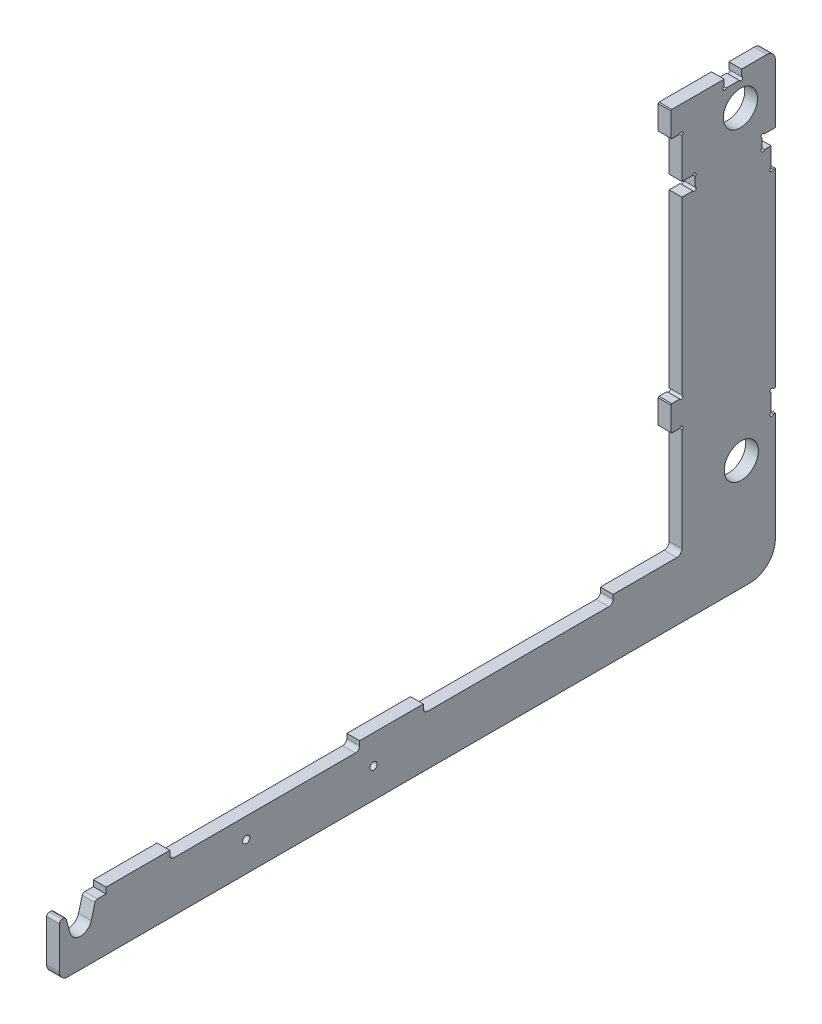
SolidWorks part; units mm, degrees
material "S355J2H"
ref_plane "Front Plane" through (0, 0, 0) normal (0, 0, 1) x (1, 0, 0)
ref_plane "Top Plane" through (0, 0, 0) normal (0, 1, 0) x (1, 0, 0)
ref_plane "Right Plane" through (0, 0, 0) normal (1, 0, 0) x (0, 0, -1)
sketch "Sketch1" plane through (0, 0, 0) normal (1, 0, 0) x (0, 0, -1)
  line L0 (-678, 0) -> (0, 0)
  line L1 (0, 0) -> (0, 460)
  line L2 (-678, 0) -> (-678, -69)
  line L4 (-678, -69) -> (110, -69)
  line L5 (110, -69) -> (110, 460)
  line L6 (110, 460) -> (0, 460)
  dimension "D1" = 678
  dimension "D2" = 460
  dimension "D3" = 110
  dimension "D4" = 69
extrude "Boss-Extrude1" add sketch "Sketch1" along normal blind 15
fillet "Fillet1" radius 30 1 edges at (7.5, -69, -110)
sketch "Sketch2" plane through (15, 0, 0) normal (1, 0, 0) x (0, 0, -1)
  line L0 (110, -39) -> (110, 460) construction
  line L2 (-678, -69) -> (80, -69) construction
  circle A0 centre (68.9, 421) radius 20.1
  circle A1 centre (69.9, 61) radius 20.1
  dimension "D1" = 40.2
  dimension "D2" = 41.1
  dimension "D5" = 40.1
  dimension "D3" = 130
  dimension "D4" = 490
extrude "Cut-Extrude1" cut sketch "Sketch2" against normal through all
fillet "Fillet2" radius 6 1 edges at (7.5, 0, 0)
sketch "Sketch4" plane through (0, 0, 0) normal (0, 0, 1) x (1, 0, 0)
  line L0 (15, 460) -> (15, 6) construction
  line L1 (0, 460) -> (15, 460)
  line L2 (0, 460) -> (0, 430)
  line L3 (0, 430) -> (15, 430)
  line L4 (15, 460) -> (15, 430)
  line L5 (0, 460) -> (0, 6) construction
  line L6 (0, 160) -> (15, 160)
  line L7 (0, 160) -> (0, 130)
  line L8 (0, 130) -> (15, 130)
  line L9 (15, 160) -> (15, 130)
  dimension "D1" = 30
  dimension "D2" = 300
extrude "Boss-Extrude2" add sketch "Sketch4" along normal blind 13
fillet "Fillet3" radius 10 1 edges at (7.5, 460, -110)
sketch "Sketch5" plane through (0, 0, 0) normal (-1, 0, 0) x (0, 0, 1)
  line L0 (-100, 460) -> (13, 460) construction
  line L1 (-70.25, 460) -> (-49.75, 460)
  line L2 (-70.25, 460) -> (-70.25, 449.75)
  line L3 (-70.25, 449.75) -> (-49.75, 449.75)
  line L4 (-49.75, 460) -> (-49.75, 449.75)
  line L5 (-110, -39) -> (-110, 450) construction
  dimension "D1" = 39.75
  dimension "D2" = 10.25
  dimension "D3" = 20.5
extrude "Cut-Extrude3" cut sketch "Sketch5" against normal through all
sketch "Sketch6" plane through (15, 0, 0) normal (1, 0, 0) x (0, 0, -1)
  line L0 (110, -39) -> (110, 450) construction
  line L1 (110, 380.5) -> (94.5, 380.5)
  line L2 (110, 380.5) -> (110, 364.5)
  line L3 (110, 364.5) -> (94.5, 364.5)
  line L4 (94.5, 380.5) -> (94.5, 364.5)
  line L5 (100, 460) -> (70.25, 460) construction
  line L6 (0, 430) -> (0, 160) construction
  line L7 (0, 380.5) -> (15.5, 380.5)
  line L8 (0, 380.5) -> (0, 364.5)
  line L9 (0, 364.5) -> (15.5, 364.5)
  line L10 (15.5, 380.5) -> (15.5, 364.5)
  line L11 (15.5, 380.5) -> (94.5, 380.5) construction
  dimension "D1" = 16
  dimension "D2" = 79.5
  dimension "D3" = 15.5
extrude "Cut-Extrude4" cut sketch "Sketch6" against normal through all
sketch "Sketch7" plane through (0, 0, 0) normal (-1, 0, 0) x (0, 0, 1)
  line L0 (-110, -39) -> (-110, 364.5) construction
  line L1 (-110, 364.5) -> (-105, 364.5)
  line L2 (-110, 364.5) -> (-110, 339)
  line L3 (-110, 339) -> (-105, 339)
  line L4 (-105, 364.5) -> (-105, 339)
  line L6 (-105, 89.5) -> (-105, 115.5)
  line L7 (-110, 115.5) -> (-105, 115.5)
  line L8 (-110, 89.5) -> (-110, 115.5)
  line L9 (-110, 89.5) -> (-105, 89.5)
  dimension "D1" = 25.5
  dimension "D2" = 5
  dimension "D3" = 275
  dimension "D4" = 26
  dimension "D5" = 5
extrude "Cut-Extrude5" cut sketch "Sketch7" against normal through all
chamfer "Chamfer1" distance 1 angle 45 4 edges at (7.5, 460, 13) (7.5, 130, 13) (7.5, 160, 13) (7.5, 430, 13)
sketch "Sketch8" plane through (15, 0, 0) normal (1, 0, 0) x (0, 0, -1)
  line L0 (-6, 0) -> (-678, 0) construction
  line L1 (-603, 0) -> (-379.5, 0)
  line L2 (-603, 0) -> (-603, -10)
  line L3 (-603, -10) -> (-379.5, -10)
  line L4 (-379.5, 0) -> (-379.5, -10)
  line L5 (-678, 0) -> (-678, -69) construction
  line L6 (-342, 0) -> (-342, -239.7246) construction
  line L7 (-304.5, 0) -> (-304.5, -10)
  line L8 (-81, -10) -> (-304.5, -10)
  line L9 (-81, 0) -> (-81, -10)
  line L10 (-81, 0) -> (-304.5, 0)
  dimension "D1" = 75
  dimension "D2" = 10
  dimension "D3" = 37.5
extrude "Cut-Extrude6" cut sketch "Sketch8" against normal up to surface (15 mm away) up to face at (0, 421, -89)
fillet "Fillet4" radius 5 4 edges at (7.5, -10, 603) (7.5, -10, 379.5) (7.5, -10, 304.5) (7.5, -10, 81)
sketch "Sketch9" plane through (15, 0, 0) normal (1, 0, 0) x (0, 0, -1)
  line L0 (-0.7071, 129.2929) -> (0, 130) construction
  line L1 (-12, 130) -> (0, 130) construction
  line L2 (-13, 145) -> (35.3065, 145) construction
  line L3 (-13, 131) -> (-13, 159) construction
  line L4 (-0.7071, 160.7071) -> (0, 160) construction
  line L5 (-0.7071, 429.2929) -> (0, 430) construction
  line L6 (-12, 430) -> (0, 430) construction
  circle A0 centre (-0.7071, 129.2929) radius 2
  circle A1 centre (-0.7071, 160.7071) radius 2
  circle A2 centre (-0.7071, 429.2929) radius 2
  dimension "D2" = 4
  dimension "D5" = 4
  dimension "D1" = 1
  dimension "D3" = 45
  dimension "D4" = 1
  dimension "D6" = 45
extrude "Cut-Extrude7" cut sketch "Sketch9" against normal through all
sketch "Sketch10" plane through (15, 0, 0) normal (1, 0, 0) x (0, 0, -1)
  line L0 (50.4571, 450.4571) -> (49.75, 449.75) construction
  line L1 (49.75, 449.75) -> (49.75, 460) construction
  line L2 (60, 449.75) -> (60, 463.7906) construction
  line L3 (70.25, 449.75) -> (49.75, 449.75) construction
  line L4 (69.5429, 450.4571) -> (70.25, 449.75) construction
  circle A0 centre (50.4571, 450.4571) radius 2
  circle A1 centre (69.5429, 450.4571) radius 2
  dimension "D2" = 4
  dimension "D1" = 1
  dimension "D3" = 45
extrude "Cut-Extrude8" cut sketch "Sketch10" against normal through all
sketch "Sketch11" plane through (15, 0, 0) normal (1, 0, 0) x (0, 0, -1)
  line L0 (14.7929, 365.2071) -> (15.5, 364.5) construction
  line L1 (0, 364.5) -> (15.5, 364.5) construction
  line L2 (15.5, 372.5) -> (-13.4221, 372.5) construction
  line L3 (15.5, 364.5) -> (15.5, 380.5) construction
  line L4 (14.7929, 379.7929) -> (15.5, 380.5) construction
  line L5 (55, 392.5692) -> (55, 339.5302) construction
  line L6 (95.2071, 379.7929) -> (94.5, 380.5) construction
  line L7 (94.5, 372.5) -> (123.4221, 372.5) construction
  line L8 (95.2071, 365.2071) -> (94.5, 364.5) construction
  circle A0 centre (14.7929, 365.2071) radius 2
  circle A1 centre (14.7929, 379.7929) radius 2
  circle A2 centre (95.2071, 379.7929) radius 2
  circle A3 centre (95.2071, 365.2071) radius 2
  dimension "D2" = 4
  dimension "D1" = 1
  dimension "D3" = 45
extrude "Cut-Extrude9" cut sketch "Sketch11" against normal through all
sketch "Sketch12" plane through (15, 0, 0) normal (1, 0, 0) x (0, 0, -1)
  line L0 (105.7071, 90.2071) -> (105, 89.5) construction
  line L1 (110, 89.5) -> (105, 89.5) construction
  line L2 (105, 102.5) -> (129.1199, 102.5) construction
  line L3 (105, 89.5) -> (105, 115.5) construction
  line L4 (105.7071, 114.7929) -> (105, 115.5) construction
  line L5 (105.7071, 339.7071) -> (105, 339) construction
  line L6 (105, 339) -> (105, 364.5) construction
  line L7 (110, 339) -> (105, 339) construction
  circle A0 centre (105.7071, 90.2071) radius 2
  circle A1 centre (105.7071, 114.7929) radius 2
  circle A2 centre (105.7071, 339.7071) radius 2
  dimension "D2" = 4
  dimension "D5" = 4
  dimension "D1" = 1
  dimension "D3" = 45
  dimension "D4" = 1
  dimension "D6" = 45
extrude "Cut-Extrude10" cut sketch "Sketch12" against normal through all
sketch "Sketch13" plane through (15, 0, 0) normal (1, 0, 0) x (0, 0, -1)
  line L0 (-678, -69) -> (-733, -69)
  line L1 (-733, -69) -> (-733, -7)
  line L2 (-733, -7) -> (-725.5, -7)
  line L3 (-725.5, -7) -> (-720.5532, -25.3788)
  line L4 (-695.4468, -25.3788) -> (-690.5, -7)
  line L5 (-690.5, -7) -> (-678, -7)
  line L6 (-678, -7) -> (-678, -69)
  line L7 (-678, 0) -> (-678, -69) construction
  line L8 (-603, 0) -> (-678, 0) construction
  arc A0 (-720.5532, -25.3788) -> (-695.4468, -25.3788) centre (-708, -22) ccw
  dimension "D1" = 55
  dimension "D3" = 13
  dimension "D2" = 25
  dimension "D4" = 15
  dimension "D5" = 35
  dimension "D6" = 7
extrude "Boss-Extrude3" add sketch "Sketch13" against normal blind 15
fillet "Fillet5" radius 10 1 edges at (7.5, -69, 733)
fillet "Fillet6" radius 3 3 edges at (7.5, -7, 733) (7.5, -7, 725.5) (7.5, -7, 690.5)
sketch "Sketch14" plane through (15, 0, 0) normal (1, 0, 0) x (0, 0, -1)
  line L0 (-513, -34) -> (-363, -34) construction
  line L1 (-723, -69) -> (80, -69) construction
  line L2 (-733, -10) -> (-733, -59) construction
  circle A0 centre (-513, -34) radius 4.25
  circle A1 centre (-363, -34) radius 4.25
  dimension "D1" = 8.5
  dimension "D2" = 150
  dimension "D3" = 35
  dimension "D4" = 220
extrude "Cut-Extrude11" cut sketch "Sketch14" against normal through all
